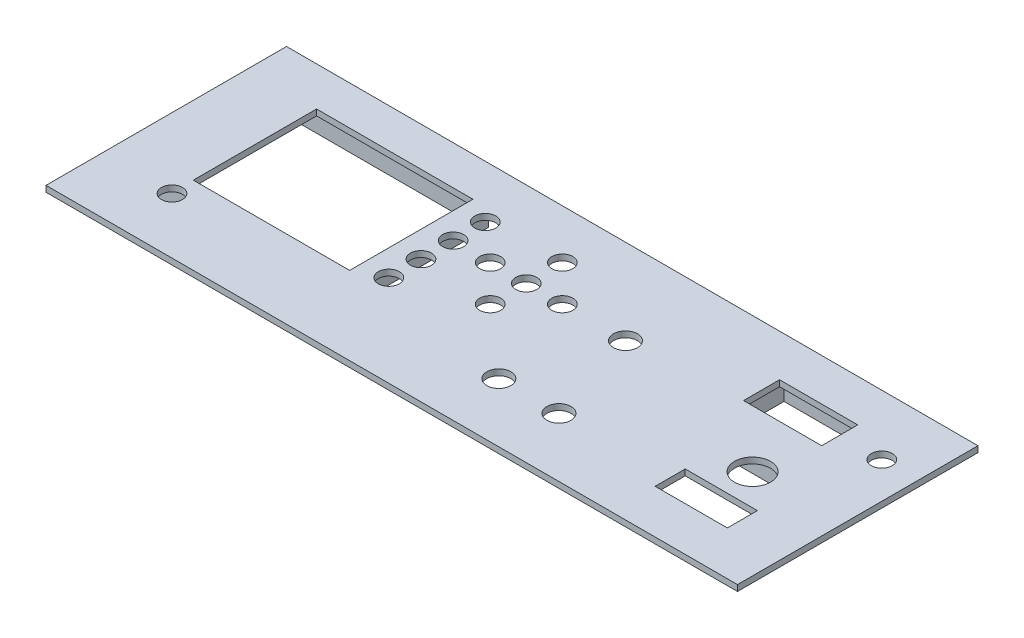
SolidWorks part; units mm, degrees
ref_plane "前视基准面" through (0, 0, 0) normal (0, 0, 1) x (1, 0, 0)
ref_plane "上视基准面" through (0, 0, 0) normal (0, 1, 0) x (1, 0, 0)
ref_plane "右视基准面" through (0, 0, 0) normal (1, 0, 0) x (0, 0, -1)
sketch "草图1" plane through (0, 0, 0) normal (0, 1, 0) x (1, 0, 0)
  line L0 (-7.8118, 40.8962) -> (-7.8118, -24.9038) construction
  line L5 (-68.4318, 34.2718) -> (-16.4318, 34.2718)
  line L6 (-68.4318, 34.2718) -> (-68.4318, -6.7282)
  line L7 (-68.4318, -6.7282) -> (-16.4318, -6.7282)
  line L8 (-16.4318, 34.2718) -> (-16.4318, -6.7282)
  line L9 (16.6882, 40.8962) -> (16.6882, -24.9038) construction
  line L10 (-1.2935, 18.8962) -> (82.6058, 18.8962) construction
  line L11 (79.3457, -13.1032) -> (32.214, -13.1032) construction
  line L13 (-91.4318, 47.2718) -> (138.5682, 47.2718)
  line L14 (-91.4318, 47.2718) -> (-91.4318, -32.7282)
  line L15 (-91.4318, -32.7282) -> (138.5682, -32.7282)
  line L16 (138.5682, 47.2718) -> (138.5682, -32.7282)
  line L17 (86.5682, 33.2718) -> (112.5682, 33.2718)
  line L18 (86.5682, 33.2718) -> (86.5682, 21.2718)
  line L19 (86.5682, 21.2718) -> (112.5682, 21.2718)
  line L20 (112.5682, 33.2718) -> (112.5682, 21.2718)
  line L21 (96.5682, -8.1032) -> (120.5682, -8.1032)
  line L22 (96.5682, -8.1032) -> (96.5682, -18.1032)
  line L23 (96.5682, -18.1032) -> (120.5682, -18.1032)
  line L24 (120.5682, -8.1032) -> (120.5682, -18.1032)
  circle A0 centre (-68.1318, -14.1282) radius 3.5
  circle A1 centre (-7.8118, 29.7718) radius 3.5
  circle A2 centre (-7.8118, 19.0718) radius 3.5
  circle A3 centre (-7.8118, 8.3718) radius 3.5
  circle A4 centre (-7.8118, -2.3282) radius 3.5
  circle A5 centre (16.6882, 30.8962) radius 3.5
  circle A6 centre (16.6882, 18.8962) radius 3.5
  circle A7 centre (16.6882, 6.8962) radius 3.5
  circle A8 centre (4.6882, 18.8962) radius 3.5
  circle A9 centre (28.6882, 18.8962) radius 3.5
  circle A10 centre (49.6882, 18.8962) radius 4
  circle A11 centre (59.5682, -13.1032) radius 4
  circle A12 centre (39.5682, -13.1032) radius 4
  circle A13 centre (126.5682, 27.2718) radius 3.5
  circle A14 centre (108.5682, 2.2718) radius 6
  point P46 (-91.4318, 7.2718)
  point P47 (-80.6543, 7.2718)
  point P50 (96.5682, -13.1032)
  point P53 (112.5682, 27.2718)
  point P58 (108.5682, -8.1032)
  dimension "D7" = 12
  dimension "D10" = 19.625
  dimension "D14" = 12
  dimension "D16" = 131
  dimension "D19" = 20
  dimension "D29" = 30
  dimension "D24" = 26
  dimension "D26" = 14
  dimension "D3" = 52
  dimension "D4" = 41
  dimension "D5" = 23
  dimension "D6" = 13
  dimension "D8" = 21
  dimension "D9" = 8.62
  dimension "D11" = 10.7
  dimension "D12" = 10.7
  dimension "D13" = 10.7
  dimension "D15" = 12
  dimension "D17" = 12
  dimension "D18" = 12.5
  dimension "D20" = 7.4
  dimension "D21" = 23.3
  dimension "D22" = 80
  dimension "D23" = 230
  dimension "D25" = 12
  dimension "D27" = 12
  dimension "D28" = 20
  dimension "D30" = 45
  dimension "D31" = 24
  dimension "D32" = 10
  dimension "D33" = 17.5
  dimension "D34" = 28.3756
extrude "凸台-拉伸1" add sketch "草图1" along normal blind 2
sketch "草图3" plane through (0, 0, 0) normal (0, -1, 0) x (1, 0, 0)
  line L0 (-91.4318, 32.7282) -> (138.5682, 32.7282) construction
  line L1 (-78.4318, 8.2282) -> (-15.2318, 8.2282)
  line L2 (-78.4318, 8.2282) -> (-78.4318, -35.2718)
  line L3 (-78.4318, -35.2718) -> (-15.2318, -35.2718)
  line L4 (-15.2318, 8.2282) -> (-15.2318, -35.2718)
  line L5 (138.5682, -47.2718) -> (-91.4318, -47.2718) construction
  line L6 (-16.4318, 6.7282) -> (-16.4318, -34.2718) construction
  line L7 (-91.4318, -47.2718) -> (-91.4318, 32.7282) construction
  line L9 (-79.9318, 9.7282) -> (-13.7318, 9.7282)
  line L10 (-79.9318, 9.7282) -> (-79.9318, -36.7718)
  line L11 (-79.9318, -36.7718) -> (-13.7318, -36.7718)
  line L12 (-13.7318, 9.7282) -> (-13.7318, -36.7718)
  line L13 (85.5682, -11.2718) -> (113.5682, -11.2718)
  line L14 (85.5682, -11.2718) -> (85.5682, -35.7718)
  line L15 (85.5682, -35.7718) -> (113.5682, -35.7718)
  line L16 (113.5682, -11.2718) -> (113.5682, -35.7718)
  line L19 (112.5682, -33.2718) -> (86.5682, -33.2718) construction
  line L25 (84.0682, -9.7718) -> (115.0682, -9.7718)
  line L26 (84.0682, -9.7718) -> (84.0682, -37.2718)
  line L27 (84.0682, -37.2718) -> (115.0682, -37.2718)
  line L28 (115.0682, -9.7718) -> (115.0682, -37.2718)
  point P20 (126.5682, -27.2718)
  point P21 (99.5682, -33.2718)
  point P23 (86.3228, -5.7329)
  point P25 (99.5682, -35.7718)
  dimension "D1" = 24.5
  dimension "D2" = 12
  dimension "D3" = 1.2
  dimension "D4" = 13
  dimension "D5" = 1.5
  dimension "D6" = 1.5
  dimension "D7" = 1.5
  dimension "D8" = 1.5
  dimension "D9" = 28
  dimension "D10" = 24.5
  dimension "D11" = 2.5
  dimension "D12" = 1.5
  dimension "D13" = 1.5
  dimension "D14" = 1.5
  dimension "D15" = 1.5
extrude "凸台-拉伸2" add sketch "草图3" along normal blind 6
